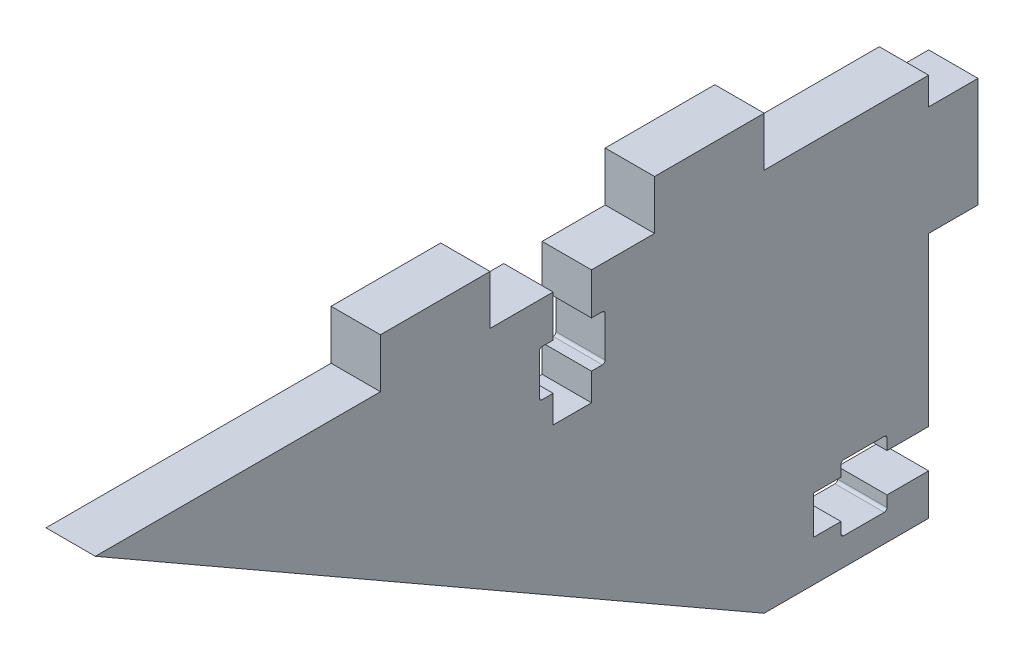
SolidWorks part; units mm, degrees
ref_plane "Front Plane" through (0, 0, 0) normal (0, 0, 1) x (1, 0, 0)
ref_plane "Top Plane" through (0, 0, 0) normal (0, 1, 0) x (1, 0, 0)
ref_plane "Right Plane" through (0, 0, 0) normal (1, 0, 0) x (0, 0, -1)
sketch "Sketch1" plane through (0, 0, 0) normal (1, 0, 0) x (0, 0, -1)
  line L0 (0, 0) -> (0, -35)
  line L1 (0, -35) -> (-76, 0)
  line L2 (-76, 0) -> (0, 0)
  dimension "D1" = 35
  dimension "D2" = 76
extrude "Boss-Extrude1" add sketch "Sketch1" along normal blind 4.5
sketch "Sketch2" plane through (4.5, 0, 0) normal (1, 0, 0) x (0, 0, -1)
  line L0 (0, -35) -> (0, 0) construction
  line L1 (-4.5, -2.5) -> (4.5, -2.5)
  line L2 (-4.5, -2.5) -> (-4.5, -12.5)
  line L3 (-4.5, -12.5) -> (4.5, -12.5)
  line L4 (4.5, -2.5) -> (4.5, -12.5)
  line L5 (-4.5, -2.5) -> (4.5, -12.5) construction
  line L6 (-4.5, -12.5) -> (4.5, -2.5) construction
  line L7 (0, 0) -> (-76, 0) construction
  point P0 (0, -7.5)
  dimension "D1" = 10
  dimension "D2" = 7.5
  dimension "D3" = 4.5
extrude "Boss-Extrude2" add sketch "Sketch2" against normal through all
sketch "Sketch3" plane through (4.5, 0, 0) normal (1, 0, 0) x (0, 0, -1)
  line L0 (0, -35) -> (-15, -35)
  line L1 (0, -25) -> (-76, 0)
  line L4 (0, -35) -> (0, -12.5) construction
  line L5 (0, -25) -> (0, -35)
  line L6 (-76, 0) -> (-15, -35)
  dimension "D1" = 15
  dimension "D2" = 10
extrude "Boss-Extrude3" add sketch "Sketch3" against normal through all
sketch "Sketch4" plane through (4.5, 0, 0) normal (1, 0, 0) x (0, 0, -1)
  line L0 (0, -29.5) -> (-10.5, -29.5) construction
  line L1 (0, -35) -> (0, -12.5) construction
  line L2 (0, -27.75) -> (-10.5, -27.75) construction
  line L3 (-10.5, -27.75) -> (-10.5, -31.25) construction
  line L4 (0, -31.25) -> (0, -27.75)
  line L5 (0, -27.75) -> (-3.8, -27.75)
  line L6 (-3.8, -27.75) -> (-3.8, -26.75)
  line L7 (-4.05, -26.5) -> (-7.75, -26.5)
  line L8 (-8, -26.75) -> (-8, -27.75)
  line L9 (-8, -27.75) -> (-10.5, -27.75)
  line L10 (-10.5, -27.75) -> (-10.5, -31.25)
  line L12 (0, -31.25) -> (-10.5, -31.25) construction
  line L13 (-8, -31.25) -> (-10.5, -31.25)
  line L14 (-8, -32.25) -> (-8, -31.25)
  line L15 (-4.05, -32.5) -> (-7.75, -32.5)
  line L16 (-3.8, -31.25) -> (-3.8, -32.25)
  line L17 (0, -31.25) -> (-3.8, -31.25)
  line L18 (4.5, -12.5) -> (4.5, -2.5) construction
  line L19 (0, -18.5) -> (-43.7571, -18.5) construction
  line L20 (-76, 0) -> (-15, -35) construction
  line L37 (0, -31.25) -> (-10.5, -31.25) construction
  arc A0 (-8, -32.25) -> (-7.75, -32.5) centre (-7.75, -32.25) ccw
  arc A1 (-4.05, -32.5) -> (-3.8, -32.25) centre (-4.05, -32.25) ccw
  arc A2 (-3.8, -26.75) -> (-4.05, -26.5) centre (-4.05, -26.75) ccw
  arc A3 (-7.75, -26.5) -> (-8, -26.75) centre (-7.75, -26.75) ccw
  point P10 (4.5, -7.5)
  point P20 (-8, -32.5)
  point P23 (-3.8, -32.5)
  point P26 (-3.8, -26.5)
  point P29 (-8, -26.5)
  dimension "D7" = 0.25
  dimension "D1" = 10.5
  dimension "D2" = 1.75
  dimension "D3" = 3
  dimension "D4" = 4.2
  dimension "D5" = 8
  dimension "D6" = 22
extrude "Cut-Extrude1" cut sketch "Sketch4" against normal through all
sketch "Sketch5" plane through (4.5, 0, 0) normal (1, 0, 0) x (0, 0, -1)
  line L0 (0, 0) -> (-76, 0) construction
  line L1 (-25, 4.5) -> (-15, 4.5)
  line L2 (-25, 4.5) -> (-25, -4.5)
  line L3 (-25, -4.5) -> (-15, -4.5)
  line L4 (-15, 4.5) -> (-15, -4.5)
  line L5 (-25, 4.5) -> (-15, -4.5) construction
  line L6 (-25, -4.5) -> (-15, 4.5) construction
  line L7 (-32.5, 0) -> (-32.5, 4.5) construction
  line L8 (-40, -4.5) -> (-50, 4.5) construction
  line L9 (-40, 4.5) -> (-50, -4.5) construction
  line L10 (-50, 4.5) -> (-50, -4.5)
  line L11 (-40, -4.5) -> (-50, -4.5)
  line L12 (-40, 4.5) -> (-40, -4.5)
  line L13 (-40, 4.5) -> (-50, 4.5)
  line L14 (-25, -4.5) -> (-15, 4.5) construction
  point P0 (-20, 0)
  point P14 (-45, 0)
  dimension "D3" = 4.5
  dimension "D1" = 20
  dimension "D2" = 10
  dimension "D4" = 25
extrude "Boss-Extrude4" add sketch "Sketch5" against normal through all
sketch "Sketch6" plane through (4.5, 0, 0) normal (1, 0, 0) x (0, 0, -1)
  line L0 (-32.5, 0) -> (-32.5, -10.5) construction
  line L1 (-25, 0) -> (-40, 0) construction
  line L2 (-30.75, -10.5) -> (-34.25, -10.5) construction
  line L3 (-34.25, -10.5) -> (-34.25, 0) construction
  line L4 (-30.75, 0) -> (-34.25, 0)
  line L5 (-34.25, 0) -> (-34.25, -3.8)
  line L6 (-34.25, -3.8) -> (-35.25, -3.8)
  line L7 (-35.5, -4.05) -> (-35.5, -7.75)
  line L8 (-35.25, -8) -> (-34.25, -8)
  line L9 (-34.25, -8) -> (-34.25, -10.5)
  line L10 (-34.25, -10.5) -> (-30.75, -10.5)
  line L11 (-30.75, -10.5) -> (-30.75, 0) construction
  line L12 (-30.75, -8) -> (-30.75, -10.5)
  line L13 (-29.75, -8) -> (-30.75, -8)
  line L14 (-29.5, -4.05) -> (-29.5, -7.75)
  line L15 (-30.75, -3.8) -> (-29.75, -3.8)
  line L16 (-30.75, 0) -> (-30.75, -3.8)
  arc A0 (-35.5, -7.75) -> (-35.25, -8) centre (-35.25, -7.75) ccw
  arc A1 (-35.25, -3.8) -> (-35.5, -4.05) centre (-35.25, -4.05) ccw
  arc A2 (-29.75, -3.8) -> (-29.5, -4.05) centre (-29.75, -4.05) cw
  arc A3 (-29.5, -7.75) -> (-29.75, -8) centre (-29.75, -7.75) cw
  point P12 (-35.5, -8)
  point P15 (-35.5, -3.8)
  point P26 (-29.5, -3.8)
  point P27 (-29.5, -8)
  dimension "D1" = 10.5
  dimension "D2" = 1.75
  dimension "D4" = 4.2
  dimension "D6" = 0.25
  dimension "D3" = 8
  dimension "D5" = 3
extrude "Cut-Extrude2" cut sketch "Sketch6" against normal through all
equation "\"X-ROD-SPACING\"=45"
equation "\"Y-ROD-SPACING\"=75"
equation "\"Z-ROD-SPACING\"=17.5"
equation "\"Y-BED-OFFSET\"=2"
equation "\"Y-BED-ROD-INSET\"=3.5"
equation "\"Y-BED-SCREW-SPACING\"=209"
equation "\"Y-BED-SCREW-CUTOUT-SLOT-HEIGHT\"=1"
equation "\"T-SLOT-NUT-FILLET-RADIUS\"=0.25"
equation "\"T-SLOT-SCREW-SHAFT-RADIUS\"=1.75"
equation "\"T-SLOT-SCREW-SHAFT-CUTOUT-LENGTH\"=10.5"
equation "\"T-SLOT-NUT-DEPTH\"=4.2"
equation "\"T-SLOT-NUT-WIDTH\"=3"
equation "\"T-SLOT-NUT-END-DISTANCE\"=8"
equation "\"ACRYLIC-THICKNESS\"=10"
equation "\"ACRYLIC-THICKNESS2\"=4.5"
equation "\"ACRYLIC-TAB-CUTOUT-SIZE\"=\"ACRYLIC-THICKNESS\"+\"ACRYLIC-TAB-TOLERANCE\"*2"
equation "\"ACRYLIC-TAB-WIDTH\"=\"ACRYLIC-THICKNESS\""
equation "\"ACRYLIC-M3-HOLE\"=3.2"
equation "\"SMOOTHROD-CAP-SCREW-DISTANCE\"=20"
equation "\"FRAME-WIDTH-INNER\"=370"
equation "\"NEMA17-HOLE-SPACING\"=31"
equation "\"NEMA17-CENTRAL-CUTOUT\"=22.5"
equation "\"Z-BRACKET-REACH\"=55"
equation "\"Z-ROD-INSET\"=16"
equation "\"TOP-BRACKET-SPACING\"=40"
equation "\"SMOOTHROD-X-LENGTH\"=350"
equation "\"SMOOTHROD-Y-LENGTH\"=350"
equation "\"SMOOTHROD-Z-LENGTH\"=350"
equation "\"SMOOTHROD-TIGHTENING-HEADROOM\"=1"
equation "\"LEADSCREW-Z-LENGTH\"=300"
equation "\"SCREW-LENGTH-FRAME\"=\"ACRYLIC-THICKNESS\" + 10"
equation "\"SCREW-LENGTH-MOTOR\"=\"ACRYLIC-THICKNESS\" + 5"
equation "\"SCREW-LENGTH-EXTRUDER\"=28"
equation "\"SCREW-HEAD-RADIUS\"=6"
equation "\"PRINTED-X-SMOOTHROD-DIAMETER\"=8.2"
equation "\"PRINTED-X-SMOOTHROD-CUTOUT\"=10"
equation "\"PRINTED-X-BASE-HEIGHT\"=10"
equation "\"PRINTED-LM8UU-CUTOUT-SIZE\"=16"
equation "\"PRINTED-LM8UU-CUTOUT-LENGTH\"=24.5"
equation "\"PRINTED-X-IDLER-HEIGHT\"=16"
equation "\"PSU-MOUNTING-WIDTH\"=95"
equation "\"PSU-MOUNTING-HEIGHT\"=177"
equation "\"Y-BELT-TO-ROD-DISTANCE\"=20"
equation "\"SPOOL-HOLDER-ROD-SPACING\"=150"
equation "\"ACRYLIC-X-CARRIAGE-WIDTH\"=55"
equation "\"ACRYLIC-X-CARRIAGE-HEIGHT\"=75"
equation "\"ACRYLIC-X-CARRIAGE-SCREW-SPACING-X\"=15"
equation "\"ACRYLIC-X-CARRIAGE-SCREW-SPACING-Y\"=33"
equation "\"ACRYLIC-X-CARRIAGE-CENTER-TAB-SPACING\"=14"
equation "\"ACRYLIC-X-CARRIAGE-EXTRUDER-SHELF-DEPTH\"=\"ACRYLIC-X-CARRIAGE-EXTRUDER-OFFSET\" + 30"
equation "\"D1@Boss-Extrude1\"=\"ACRYLIC-THICKNESS2\""
equation "\"D1@Sketch2\"=\"ACRYLIC-TAB-WIDTH\""
equation "\"D3@Sketch2\"=\"ACRYLIC-THICKNESS2\""
equation "\"ACRYLIC-X-CARRIAGE-LM8UU-CUTOUT-WIDTH\"=24.25"
equation "\"ACRYLIC-X-CARRIAGE-EXTRUDER-BRACE-SPACING\"=23"
equation "\"ACRYLIC-X-CARRIAGE-EXTRUDER-BRACE-HEIGHT\"=35"
equation "\"D1@Sketch1\"=\"ACRYLIC-X-CARRIAGE-EXTRUDER-BRACE-HEIGHT\""
equation "\"D1@Sketch4\"=\"T-SLOT-SCREW-SHAFT-CUTOUT-LENGTH\""
equation "\"D2@Sketch4\"=\"T-SLOT-SCREW-SHAFT-RADIUS\""
equation "\"D3@Sketch4\"=\"T-SLOT-NUT-WIDTH\""
equation "\"D4@Sketch4\"=\"T-SLOT-NUT-DEPTH\""
equation "\"D5@Sketch4\"=\"T-SLOT-NUT-END-DISTANCE\""
equation "\"D7@Sketch4\"=\"T-SLOT-NUT-FILLET-RADIUS\""
equation "\"ACRYLIC-X-CARRIAGE-EXTRUDER-BRACE-SCREW-SPACING\"=22"
equation "\"D6@Sketch4\"=\"ACRYLIC-X-CARRIAGE-EXTRUDER-BRACE-SCREW-SPACING\""
equation "\"ACRYLIC-X-CARRIAGE-EXTRUDER-BRACE-TAB-OFFSET\"=20"
equation "\"D1@Sketch5\"=\"ACRYLIC-X-CARRIAGE-EXTRUDER-BRACE-TAB-OFFSET\""
equation "\"D2@Sketch5\"=\"ACRYLIC-TAB-WIDTH\""
equation "\"D3@Sketch5\"=\"ACRYLIC-THICKNESS2\""
equation "\"ACRYLIC-X-CARRIAGE-EXTRUDER-OFFSET\"=26"
equation "\"ACRYLIC-X-CARRIAGE-EXTRUDER-ANGLE\"=90"
equation "\"D1@Sketch6\"=\"T-SLOT-SCREW-SHAFT-CUTOUT-LENGTH\""
equation "\"D2@Sketch6\"=\"T-SLOT-SCREW-SHAFT-RADIUS\""
equation "\"D3@Sketch6\"=\"T-SLOT-NUT-END-DISTANCE\""
equation "\"D4@Sketch6\"=\"T-SLOT-NUT-DEPTH\""
equation "\"D5@Sketch6\"=\"T-SLOT-NUT-WIDTH\""
equation "\"D6@Sketch6\"=\"T-SLOT-NUT-FILLET-RADIUS\""
